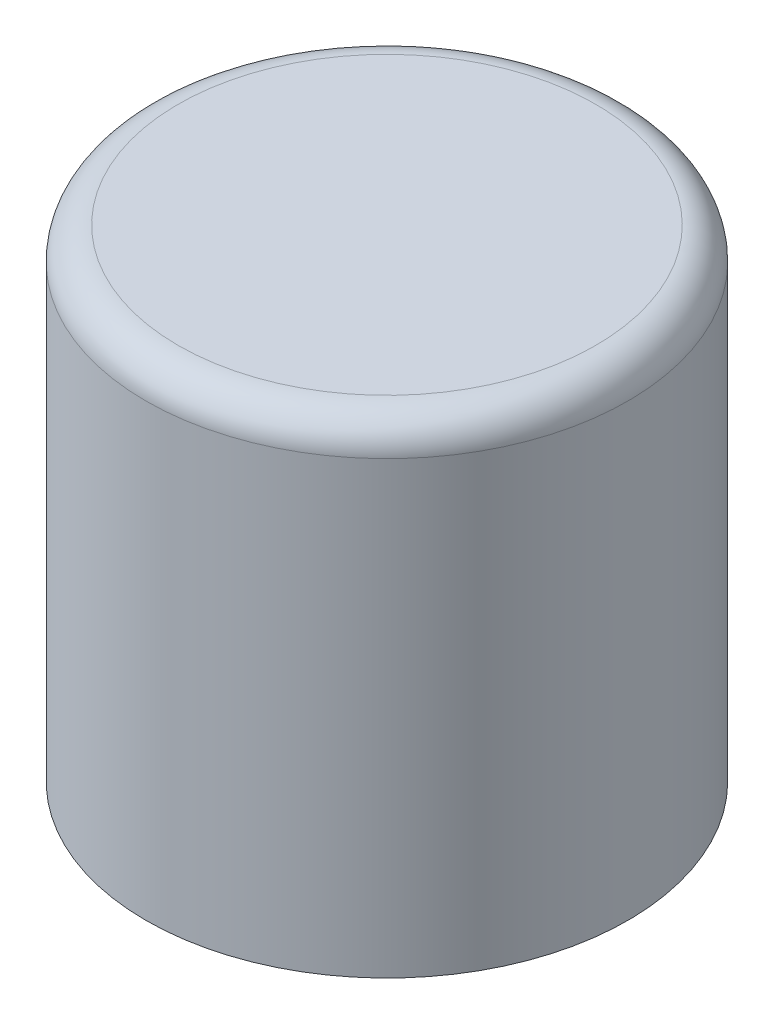
SolidWorks part; units mm, degrees
ref_plane "前视基准面" through (0, 0, 0) normal (0, 0, 1) x (1, 0, 0)
ref_plane "上视基准面" through (0, 0, 0) normal (0, 1, 0) x (1, 0, 0)
ref_plane "右视基准面" through (0, 0, 0) normal (1, 0, 0) x (0, 0, -1)
other "Configuration Table"
sketch "草图1" plane through (0, 0, 0) normal (0, 1, 0) x (1, 0, 0)
  circle A0 centre (0, 0) radius 15
  dimension "D1" = 30
extrude "凸台-拉伸1" add sketch "草图1" along normal blind 5
sketch "草图3" plane through (0, 0, 0) normal (0, 1, 0) x (1, 0, 0)
  circle A0 centre (0, 0) radius 10
  circle A1 centre (0, 0) radius 15
  circle A2 centre (0, 0) radius 15
  dimension "D1" = 0
  dimension "D2" = 5
extrude "凸台-拉伸2" add sketch "草图3" against normal blind 25
fillet "圆角1" radius 2 1 edges at (0, 5, 15)
